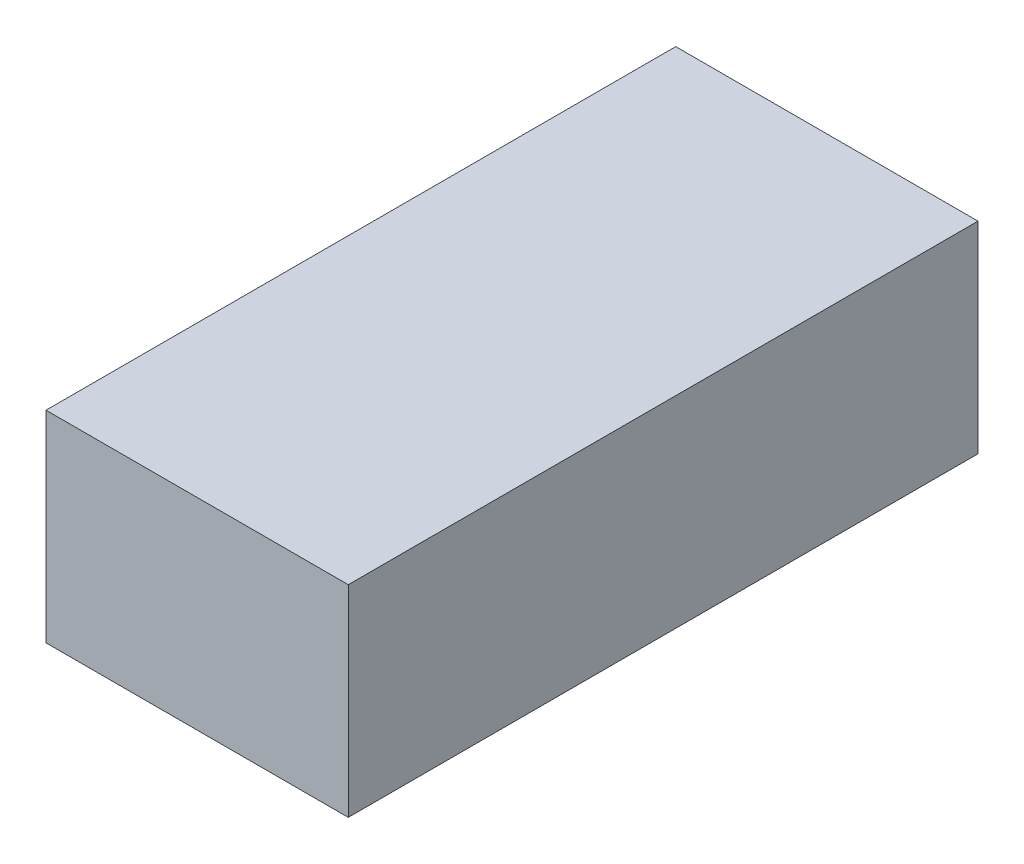
SolidWorks part; units mm, degrees
ref_plane "Front Plane" through (0, 0, 0) normal (0, 0, 1) x (1, 0, 0)
ref_plane "Top Plane" through (0, 0, 0) normal (0, 1, 0) x (1, 0, 0)
ref_plane "Right Plane" through (0, 0, 0) normal (1, 0, 0) x (0, 0, -1)
sketch "Sketch1" plane through (0, 0, 0) normal (0, 1, 0) x (1, 0, 0)
  line L1 (-4.7625, -9.9219) -> (4.7625, -9.9219)
  line L2 (-4.7625, -9.9219) -> (-4.7625, 9.9219)
  line L3 (-4.7625, 9.9219) -> (4.7625, 9.9219)
  line L4 (4.7625, -9.9219) -> (4.7625, 9.9219)
  line L5 (-4.7625, -9.9219) -> (4.7625, 9.9219) construction
  line L6 (-4.7625, 9.9219) -> (4.7625, -9.9219) construction
  point P0 (0, 0)
  dimension "D1" = 9.525
  dimension "D2" = 19.8438
extrude "Boss-Extrude1" add sketch "Sketch1" along normal blind 6.35
